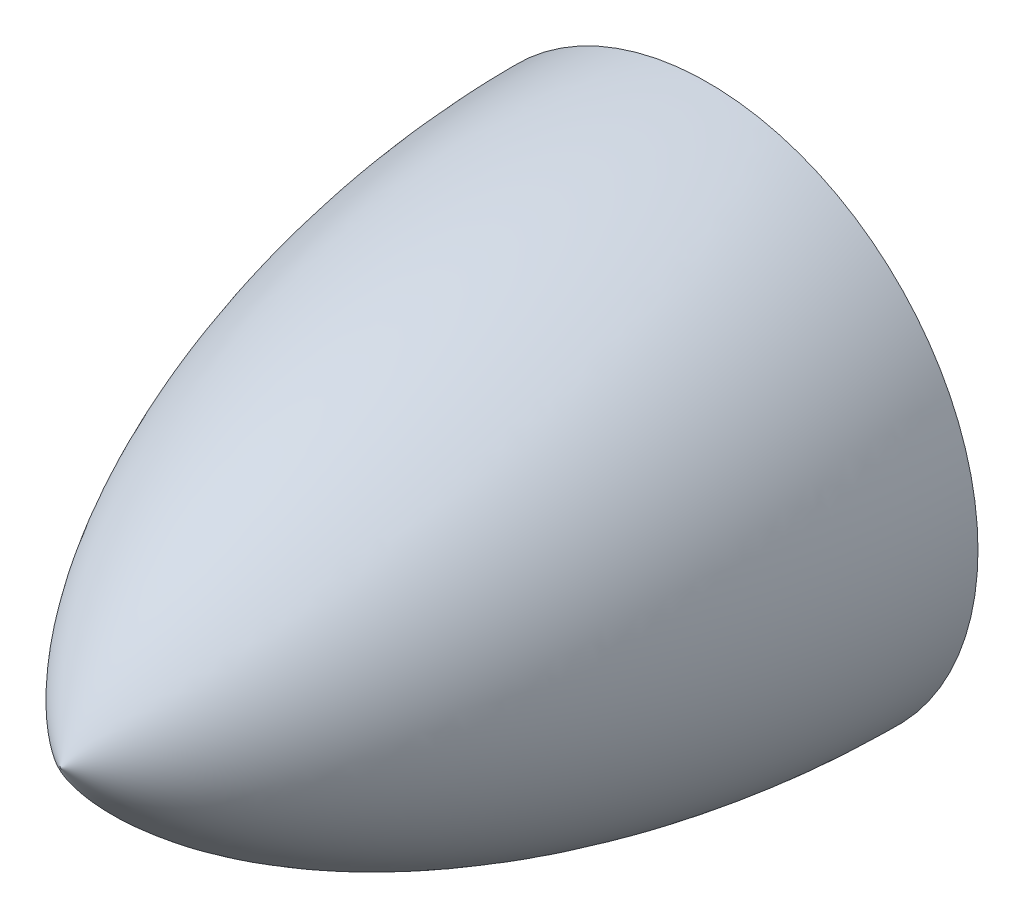
SolidWorks part; units mm, degrees
ref_plane "Front Plane" through (0, 0, 0) normal (0, 0, 1) x (1, 0, 0)
ref_plane "Top Plane" through (0, 0, 0) normal (0, 1, 0) x (1, 0, 0)
ref_plane "Right Plane" through (0, 0, 0) normal (1, 0, 0) x (0, 0, -1)
sketch "Sketch1" plane through (0, 0, 0) normal (0, 1, 0) x (1, 0, 0)
  line L0 (63.5, 0) -> (0, 0)
  line L1 (0, 0) -> (0, -152.4) construction
  line L2 (0, -152.4) -> (0, 0)
  spline S0 degree 3 poles (63.5, 0) (63.5, -63.5336) (37.7643, -130.5968) (0, -152.4) knots 0 0 0 0 1 1 1 1
  dimension "D1" = 63.5
  dimension "D2" = 152.4
revolve "Revolve1" add sketch "Sketch1" angle 360 about L1
